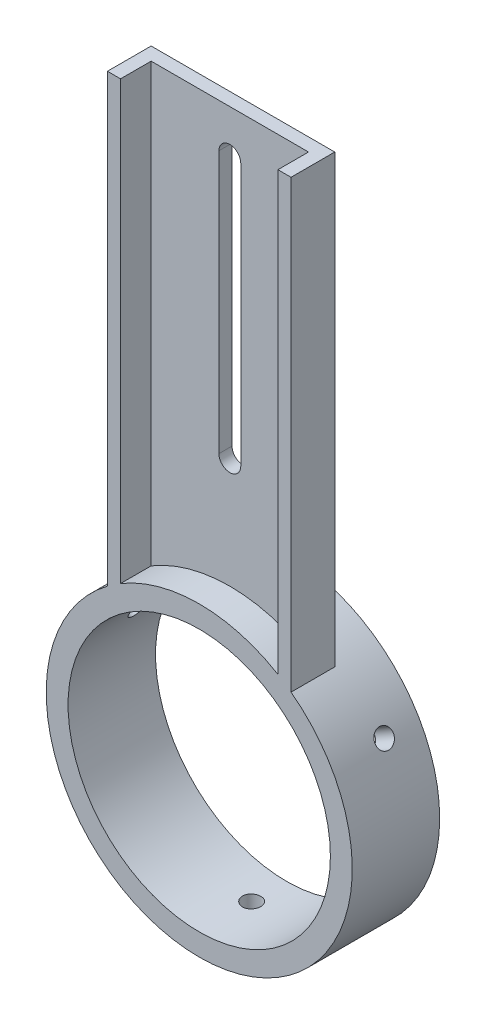
SolidWorks part; units mm, degrees
material "6061 Alloy"
ref_plane "Front Plane" through (0, 0, 0) normal (0, 0, 1) x (1, 0, 0)
ref_plane "Top Plane" through (0, 0, 0) normal (0, 1, 0) x (1, 0, 0)
ref_plane "Right Plane" through (0, 0, 0) normal (1, 0, 0) x (0, 0, -1)
sketch "Sketch1" plane through (0, 0, 0) normal (0, 0, 1) x (1, 0, 0)
  circle A0 centre (0, 0) radius 30
  circle A1 centre (0, 0) radius 35
  dimension "D1" = 60
  dimension "D2" = 70
extrude "Boss-Extrude1" add sketch "Sketch1" along normal mid plane 20
sketch "Sketch2" plane through (0, 0, 0) normal (0, 0, 1) x (1, 0, 0)
  line L0 (0, 0) -> (0, 62.4976) construction
  line L1 (-21, 130) -> (21, 130)
  line L2 (-21, 130) -> (-21, 28)
  line L3 (0, 62.4976) -> (21, 62.4976) construction
  line L4 (21, 130) -> (21, 28)
  line L5 (0, 62.4976) -> (-21, 62.4976) construction
  circle A0 centre (0, 0) radius 35 construction
  arc A1 (21, 28) -> (-21, 28) centre (0, 0) ccw
  circle A2 centre (0, 0) radius 30 construction
  dimension "D1" = 42
  dimension "D2" = 130
extrude "Boss-Extrude2" add sketch "Sketch2" along normal blind 3
sketch "Sketch3" plane through (-21, 0, 0) normal (-1, 0, 0) x (0, 0, 1)
  line L0 (10, 28) -> (10, 130)
  line L1 (0, 28) -> (10, 28)
  line L5 (10, -35) -> (10, 35) construction
  line L6 (0, 130) -> (10, 130)
  line L7 (0, 130) -> (0, 28) construction
  line L8 (0, 130) -> (0, 28)
extrude "Boss-Extrude3" add sketch "Sketch3" against normal blind 3
mirror "Mirror1" about plane through (0, 0, 0) normal (1, 0, 0) of "Boss-Extrude3"
hole_wizard "M5x0.8 Tapped Hole1" positions "Sketch5" profile "Sketch6" tap size "M5x0.8" standard "Ansi Metric"
sketch "Sketch5" plane through (0, 0, 0) normal (0, 1, 0) x (1, 0, 0)
  line L0 (35, 10) -> (-35, 10) construction
  point P0 (0, 2)
  dimension "D1" = 8
sketch "Sketch6" plane through (0, 0, -2) normal (1, 0, 0) x (0, 0, 1)
  line L0 (0, 0) -> (0, 95.3109)
  line L1 (0, 95.3109) -> (2.1, 95.3109)
  line L2 (2.1, 95.3109) -> (2.1, 0)
  line L5 (2.1, 0) -> (0, 0)
  line L11 (0, -6.35) -> (0, 107.95) construction
  dimension "Thru Tap Drill Dia." = 4.2
  dimension "Thru Tap Drill Depth" = 95.3109
cosmetic thread "Hole Thread1" parameters "D2"=5
pattern_circular "CirPattern1" count 3 over 360 about axis through (0, 0, 10) along (0, 0, -1) of "M5x0.8 Tapped Hole1"
sketch "Sketch7" plane through (0, 0, 0) normal (0, 0, -1) x (-1, 0, 0)
  line L0 (0, 120) -> (0, 60) construction
  line L1 (2.5, 120) -> (2.5, 60)
  line L2 (-2.5, 120) -> (-2.5, 60)
  line L3 (-21, 130) -> (21, 130) construction
  arc A0 (2.5, 120) -> (-2.5, 120) centre (0, 120) ccw
  arc A1 (-2.5, 60) -> (2.5, 60) centre (0, 60) ccw
  point P3 (0, 90)
  dimension "D1" = 2.5
  dimension "D3" = 10
  dimension "D2" = 60
extrude "Cut-Extrude1" cut sketch "Sketch7" against normal up to next
